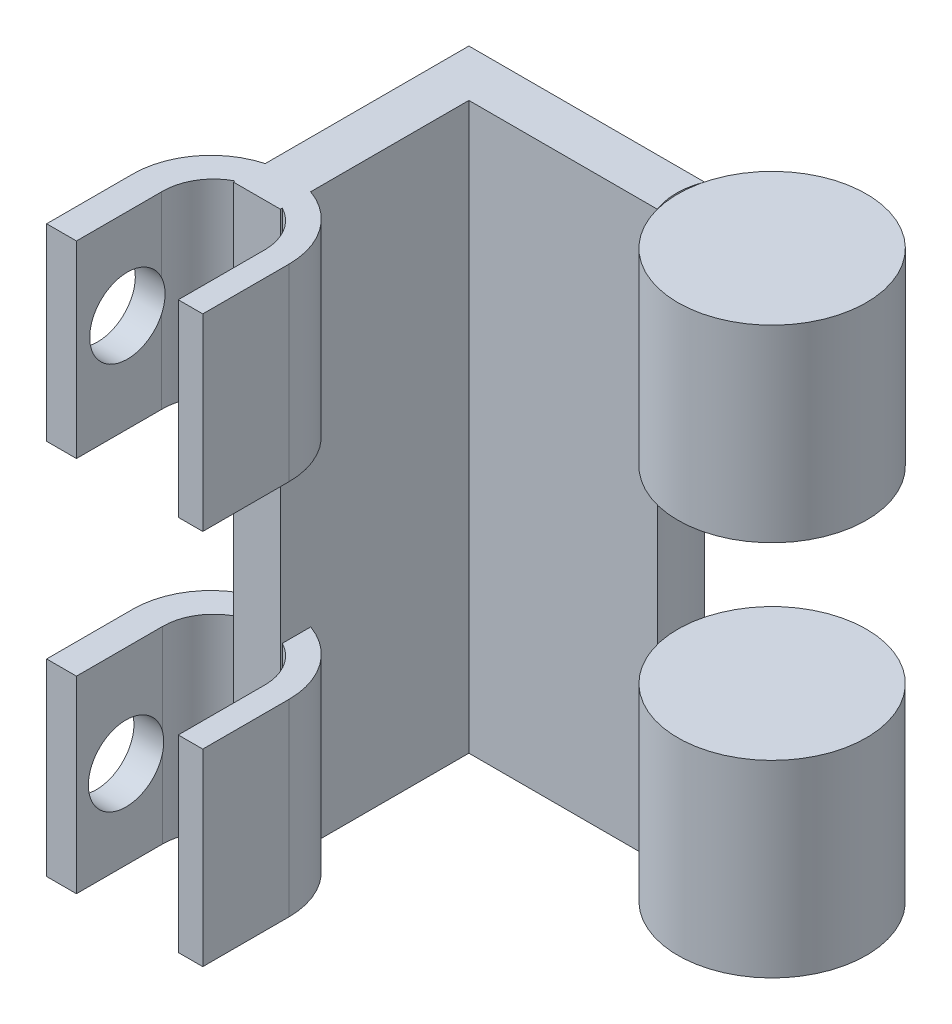
SolidWorks part; units mm, degrees
ref_plane "Front Plane" through (0, 0, 0) normal (0, 0, 1) x (1, 0, 0)
ref_plane "Top Plane" through (0, 0, 0) normal (0, 1, 0) x (1, 0, 0)
ref_plane "Right Plane" through (0, 0, 0) normal (1, 0, 0) x (0, 0, -1)
sketch "Sketch1" plane through (0, 0, 0) normal (0, 0, 1) x (1, 0, 0)
  line L1 (-136.7758, -29.1348) -> (-16.7758, -29.1348)
  line L2 (-136.7758, -29.1348) -> (-136.7758, -89.1348)
  line L3 (-136.7758, -89.1348) -> (-16.7758, -89.1348)
  line L4 (-16.7758, -29.1348) -> (-16.7758, -89.1348)
  dimension "D1" = 120
  dimension "D2" = 60
extrude "Boss-Extrude4" add sketch "Sketch1" along normal blind 5
sketch "Sketch6" plane through (0, -29.1348, 0) normal (0, 1, 0) x (1, 0, 0)
  arc A0 (-16.7758, 0) -> (-16.7758, -5) centre (-10.2374, -2.5) ccw
  dimension "D1" = 7
extrude "Cut-Extrude3" cut sketch "Sketch6" against normal blind 60 and the other way through all
sketch "Sketch18" plane through (0, -29.1348, 0) normal (0, 1, 0) x (1, 0, 0)
  circle A0 centre (-7.0933, -2.5) radius 10
  dimension "D1" = 10
extrude "Boss-Extrude9" add sketch "Sketch18" against normal blind 20 separate body
sketch "Sketch19" plane through (0, -89.1348, 0) normal (0, -1, 0) x (1, 0, 0)
  circle A0 centre (-7.0933, 2.5) radius 10
extrude "Boss-Extrude10" add sketch "Sketch19" against normal blind 20 separate body
sketch "Sketch20" plane through (0, -29.1348, 0) normal (0, 1, 0) x (1, 0, 0)
  line L0 (-16.7758, -5) -> (-136.7758, -5) construction
  line L1 (-136.7758, 0) -> (-41.7758, 0)
  line L2 (-136.7758, 0) -> (-136.7758, -5)
  line L3 (-136.7758, -5) -> (-41.7758, -5)
  line L4 (-41.7758, 0) -> (-41.7758, -5)
  dimension "D1" = 95
extrude "Cut-Extrude4" cut sketch "Sketch20" against normal blind 100
sketch "Sketch21" plane through (0, 0, 5) normal (0, 0, 1) x (1, 0, 0)
  line L0 (-41.7758, -89.1348) -> (-16.7758, -89.1348) construction
  line L1 (-41.7758, -29.1348) -> (-36.7758, -29.1348)
  line L2 (-41.7758, -29.1348) -> (-41.7758, -89.1348)
  line L3 (-41.7758, -89.1348) -> (-36.7758, -89.1348)
  line L4 (-36.7758, -29.1348) -> (-36.7758, -89.1348)
  dimension "D1" = 5
extrude "Boss-Extrude11" add sketch "Sketch21" along normal blind 20
sketch "Sketch22" plane through (0, -29.1348, 0) normal (0, 1, 0) x (1, 0, 0)
  line L0 (-47.8455, -29.5923) -> (-47.8455, -38.7434)
  line L1 (-44.6821, -29.743) -> (-44.6821, -38.7434)
  line L2 (-47.8455, -38.7434) -> (-44.6821, -38.7434)
  line L3 (-33.874, -29.4417) -> (-33.874, -38.7434)
  line L4 (-33.874, -38.7434) -> (-31.2756, -38.7434)
  line L5 (-31.2756, -38.7434) -> (-31.2756, -29.5923)
  arc A0 (-44.6821, -29.743) -> (-33.874, -29.4417) centre (-39.2781, -29.5923) cw
  arc A1 (-47.8455, -29.5923) -> (-31.2756, -29.5923) centre (-39.5605, -29.5923) cw
extrude "Boss-Extrude12" add sketch "Sketch22" against normal blind 20
sketch "Sketch24" plane through (0, -89.1348, 0) normal (0, -1, 0) x (-1, 0, 0)
  line L0 (47.8455, -29.5923) -> (47.8455, -38.7434)
  line L1 (47.8455, -38.7434) -> (44.6821, -38.7434)
  line L2 (44.6821, -38.7434) -> (44.6842, -29.5923)
  line L3 (33.874, -29.4417) -> (33.874, -38.7434)
  line L4 (33.874, -38.7434) -> (31.2756, -38.7434)
  line L5 (31.2756, -38.7434) -> (31.2756, -29.5923)
  arc A0 (47.8455, -29.5923) -> (31.2756, -29.5923) centre (39.5605, -29.5923) ccw
  arc A1 (44.6842, -29.5923) -> (33.874, -29.4417) centre (39.2781, -29.5923) ccw
  arc A2 (44.6821, -29.743) -> (41.7758, -24.7978) centre (39.2781, -29.5923) ccw construction
extrude "Boss-Extrude13" add sketch "Sketch24" against normal blind 20
sketch "Sketch25" plane through (-47.8455, 0, 0) normal (-1, 0, 0) x (0, 0, 1)
  circle A0 centre (33.3376, -38.7031) radius 4
  dimension "D1" = 8
extrude "Cut-Extrude5" cut sketch "Sketch25" against normal blind 5
sketch "Sketch26" plane through (-47.8455, 0, 0) normal (-1, 0, 0) x (0, 0, 1)
  circle A0 centre (33.48, -79.79) radius 4
  dimension "D1" = 8
extrude "Cut-Extrude6" cut sketch "Sketch26" against normal blind 5
